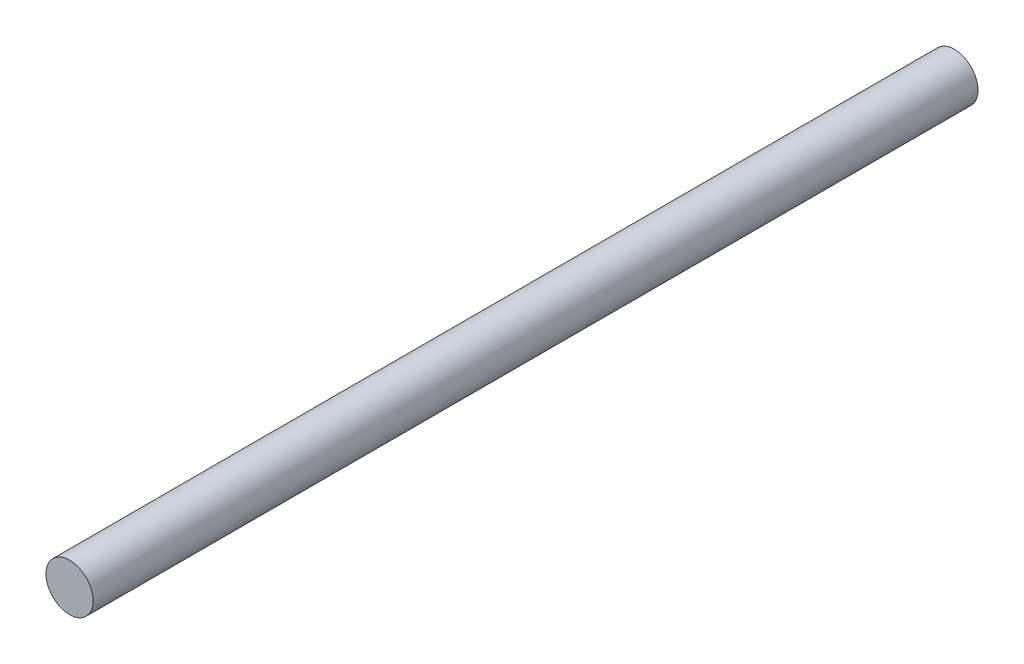
SolidWorks part; units mm, degrees
ref_plane "Front" through (0, 0, 0) normal (0, 0, 1) x (1, 0, 0)
ref_plane "Top" through (0, 0, 0) normal (0, 1, 0) x (1, 0, 0)
ref_plane "Right" through (0, 0, 0) normal (1, 0, 0) x (0, 0, -1)
sketch "Skizze1" plane through (0, 0, 0) normal (0, 0, 1) x (1, 0, 0)
  circle A0 centre (0, 0) radius 4
  dimension "D1" = 8
extrude "Aufsatz-Linear austragen1" add sketch "Skizze1" along normal blind 150
cosmetic thread "Gewindedarstellung1" parameters "D2"=6.619
thread "Gewinde1" pitch 1.25 start angle 0, offset 2, length 220, pitch 1.25, diameter 8
ref_plane "Ebene1" through (-4, 0, 152) normal (0, -1, 0) x (-1, 0, 0)
sketch "Gewindeprofil1" plane through (-4, 0, 152) normal (0, -1, 0) x (-1, 0, 0)
  line L0 (0, 0) -> (0, 1.25) construction
  line L11 (0, 0) -> (0, 1.0937)
  line L12 (0, 1.0937) -> (-0.6766, 0.7031)
  line L13 (-0.6766, 0.7031) -> (-0.6766, 0.3906)
  line L15 (-0.6766, 0.3906) -> (0, 0)
  line L17 (-0.6766, 0.5469) -> (0, 0.5469) construction
  point P2 (0, 0)
  dimension "Pitch" = 1.25
  dimension "Profile_Angle" = 60
  dimension "Profile_Land" = 0.3125
  dimension "Profile_Height" = 0.6766
